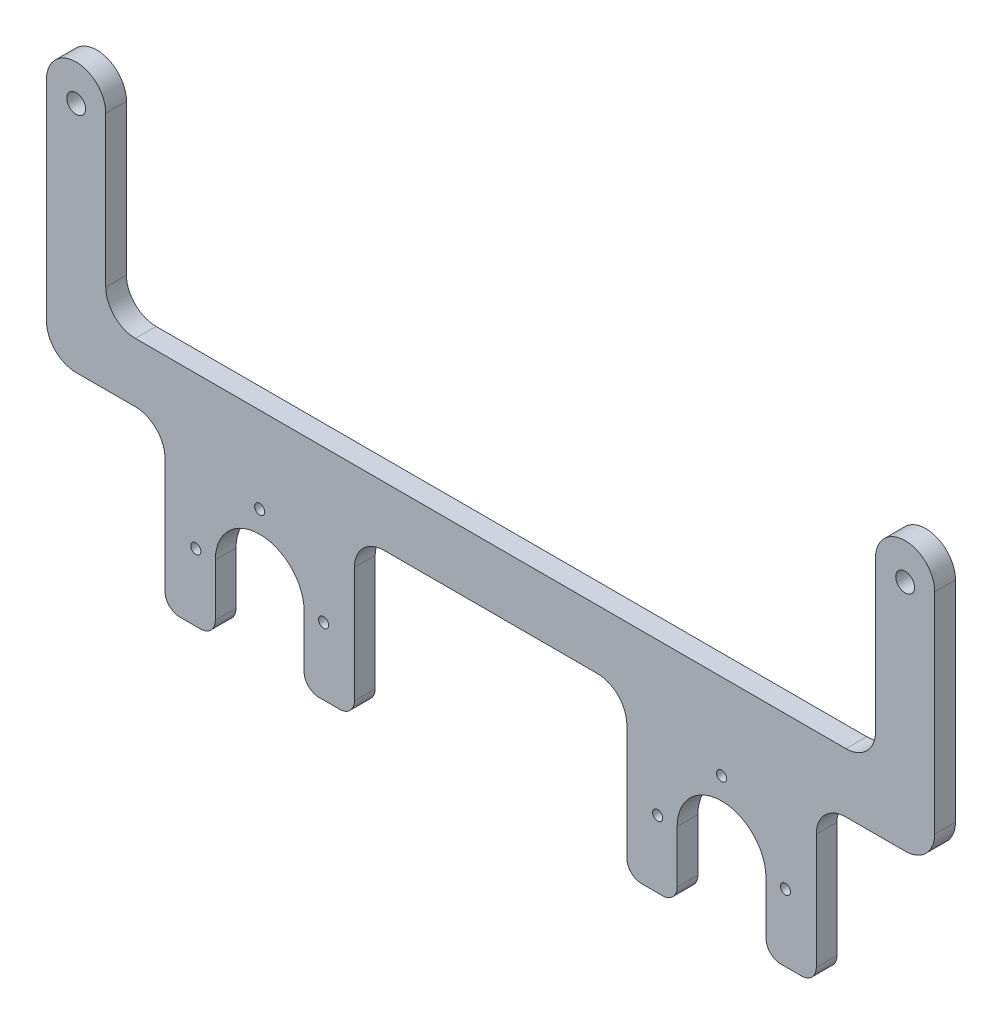
SolidWorks part; units mm, degrees
ref_plane "Front Plane" through (0, 0, 0) normal (0, 0, 1) x (1, 0, 0)
ref_plane "Top Plane" through (0, 0, 0) normal (0, 1, 0) x (1, 0, 0)
ref_plane "Right Plane" through (0, 0, 0) normal (1, 0, 0) x (0, 0, -1)
ref_plane "Plane1" through (0, 0, 7) normal (0, 0, 1) x (1, 0, 0)
sketch "Sketch1" plane through (0, 0, 7) normal (0, 0, 1) x (1, 0, 0)
  line L0 (100.4007, -62.1262) -> (107.4007, -62.1262)
  line L1 (112.4007, -57.1262) -> (112.4007, -39.4183)
  line L2 (142.4007, -39.4183) -> (142.4007, -57.1262)
  line L3 (147.4007, -62.1262) -> (154.4007, -62.1262)
  line L4 (159.4007, -57.1262) -> (159.4007, -18.1262)
  line L5 (169.4007, -8.1262) -> (189.4007, -8.1262)
  line L6 (199.4007, 1.8738) -> (199.4007, 72.7243)
  line L7 (179.4007, 72.7243) -> (179.4007, 21.8738)
  line L8 (-28.5993, -2.3531) -> (-28.5993, -89.1874) construction
  line L9 (3.4007, -18.1262) -> (3.4007, -57.1262)
  line L10 (-80.5993, 72.7243) -> (-80.5993, 21.8738)
  line L11 (-100.5993, 1.8738) -> (-100.5993, 72.7243)
  line L12 (-70.5993, -8.1262) -> (-90.5993, -8.1262)
  line L13 (-60.5993, -57.1262) -> (-60.5993, -18.1262)
  line L14 (-48.5993, -62.1262) -> (-55.5993, -62.1262)
  line L15 (-43.5993, -39.4183) -> (-43.5993, -57.1262)
  line L16 (-13.5993, -57.1262) -> (-13.5993, -39.4183)
  line L17 (-1.5993, -62.1262) -> (-8.5993, -62.1262)
  line L18 (-70.5993, 11.8738) -> (169.4007, 11.8738)
  line L19 (95.4007, -18.1262) -> (95.4007, -57.1262)
  line L20 (127.4007, -2.3531) -> (127.4007, -89.1874) construction
  line L21 (49.4007, -8.1262) -> (49.4007, -96.4791) construction
  line L22 (13.4007, -8.1262) -> (85.4007, -8.1262)
  arc A0 (95.4007, -57.1262) -> (100.4007, -62.1262) centre (100.4007, -57.1262) ccw
  arc A1 (107.4007, -62.1262) -> (112.4007, -57.1262) centre (107.4007, -57.1262) ccw
  arc A2 (112.4007, -39.4183) -> (142.4007, -39.4183) centre (127.4007, -39.4183) cw
  arc A3 (142.4007, -57.1262) -> (147.4007, -62.1262) centre (147.4007, -57.1262) ccw
  arc A4 (154.4007, -62.1262) -> (159.4007, -57.1262) centre (154.4007, -57.1262) ccw
  arc A5 (159.4007, -18.1262) -> (169.4007, -8.1262) centre (169.4007, -18.1262) cw
  arc A6 (189.4007, -8.1262) -> (199.4007, 1.8738) centre (189.4007, 1.8738) ccw
  arc A7 (199.4007, 72.7243) -> (179.4007, 72.7243) centre (189.4007, 72.7243) ccw
  arc A8 (179.4007, 21.8738) -> (169.4007, 11.8738) centre (169.4007, 21.8738) cw
  circle A9 centre (-50.1893, -39.4183) radius 1.7
  circle A10 centre (-7.0093, -39.4183) radius 1.7
  circle A11 centre (-28.5993, -17.0663) radius 1.7
  circle A12 centre (-90.5993, 70.5817) radius 3.175
  arc A13 (13.4007, -8.1262) -> (3.4007, -18.1262) centre (13.4007, -18.1262) ccw
  arc A14 (-80.5993, 21.8738) -> (-70.5993, 11.8738) centre (-70.5993, 21.8738) ccw
  arc A15 (-100.5993, 72.7243) -> (-80.5993, 72.7243) centre (-90.5993, 72.7243) cw
  arc A16 (-90.5993, -8.1262) -> (-100.5993, 1.8738) centre (-90.5993, 1.8738) cw
  arc A17 (-60.5993, -18.1262) -> (-70.5993, -8.1262) centre (-70.5993, -18.1262) ccw
  arc A18 (-55.5993, -62.1262) -> (-60.5993, -57.1262) centre (-55.5993, -57.1262) cw
  arc A19 (85.4007, -8.1262) -> (95.4007, -18.1262) centre (85.4007, -18.1262) cw
  circle A20 centre (189.4007, 70.5817) radius 3.175
  circle A21 centre (127.4007, -17.0663) radius 1.7
  circle A22 centre (105.8107, -39.4183) radius 1.7
  circle A23 centre (148.9907, -39.4183) radius 1.7
  arc A24 (-43.5993, -57.1262) -> (-48.5993, -62.1262) centre (-48.5993, -57.1262) cw
  arc A25 (-13.5993, -39.4183) -> (-43.5993, -39.4183) centre (-28.5993, -39.4183) ccw
  arc A26 (-8.5993, -62.1262) -> (-13.5993, -57.1262) centre (-8.5993, -57.1262) cw
  arc A27 (3.4007, -57.1262) -> (-1.5993, -62.1262) centre (-1.5993, -57.1262) cw
  point P82 (0, 0)
  dimension "D1" = 15
  dimension "D2" = 21.59
  dimension "D4" = 150
  dimension "D5" = 22.352
  dimension "D6" = 21.59
extrude "Boss-Extrude1" add sketch "Sketch1" against normal blind 7
